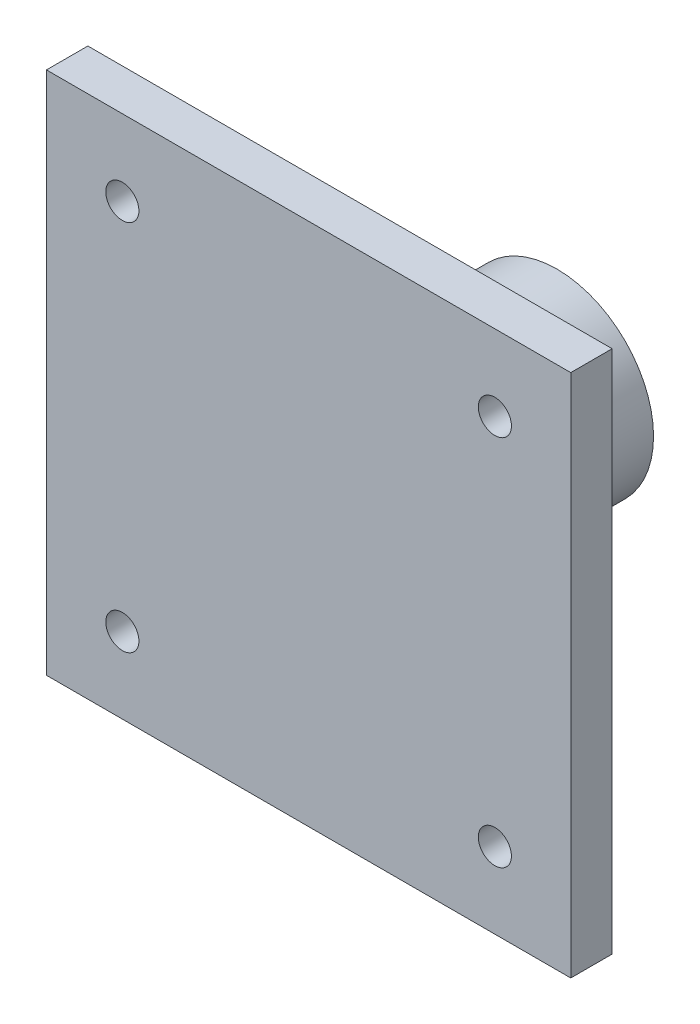
SolidWorks part; units mm, degrees
ref_plane "前视基准面" through (0, 0, 0) normal (0, 0, 1) x (1, 0, 0)
ref_plane "上视基准面" through (0, 0, 0) normal (0, 1, 0) x (1, 0, 0)
ref_plane "右视基准面" through (0, 0, 0) normal (1, 0, 0) x (0, 0, -1)
sketch "草图1" plane through (0, 0, 0) normal (0, 0, 1) x (1, 0, 0)
  line L1 (-19, 19) -> (19, 19)
  line L2 (-19, 19) -> (-19, -19)
  line L3 (-19, -19) -> (19, -19)
  line L4 (19, 19) -> (19, -19)
  line L5 (-19, 19) -> (19, -19) construction
  line L6 (-19, -19) -> (19, 19) construction
  line L7 (-13.5, 13.5) -> (13.5, 13.5) construction
  line L8 (-13.5, 13.5) -> (-13.5, -13.5) construction
  line L9 (-13.5, -13.5) -> (13.5, -13.5) construction
  line L10 (13.5, 13.5) -> (13.5, -13.5) construction
  line L11 (-13.5, 13.5) -> (13.5, -13.5) construction
  line L12 (-13.5, -13.5) -> (13.5, 13.5) construction
  circle A0 centre (-13.5, 13.5) radius 1.2
  circle A1 centre (13.5, 13.5) radius 1.2
  circle A2 centre (13.5, -13.5) radius 1.2
  circle A3 centre (-13.5, -13.5) radius 1.2
  point P0 (0, 0)
  point P6 (0, 0)
  point P21 (0, 0)
  dimension "D4" = 2.4
  dimension "D5" = 4
  dimension "D1" = 38
  dimension "D2" = 38
  dimension "D3" = 27
extrude "凸台-拉伸1" add sketch "草图1" along normal blind 3
sketch "草图2" plane through (0, 0, 0) normal (0, 0, -1) x (-1, 0, 0)
  circle A0 centre (0, 0) radius 7
  dimension "D1" = 14
extrude "凸台-拉伸2" add sketch "草图2" along normal blind 15
